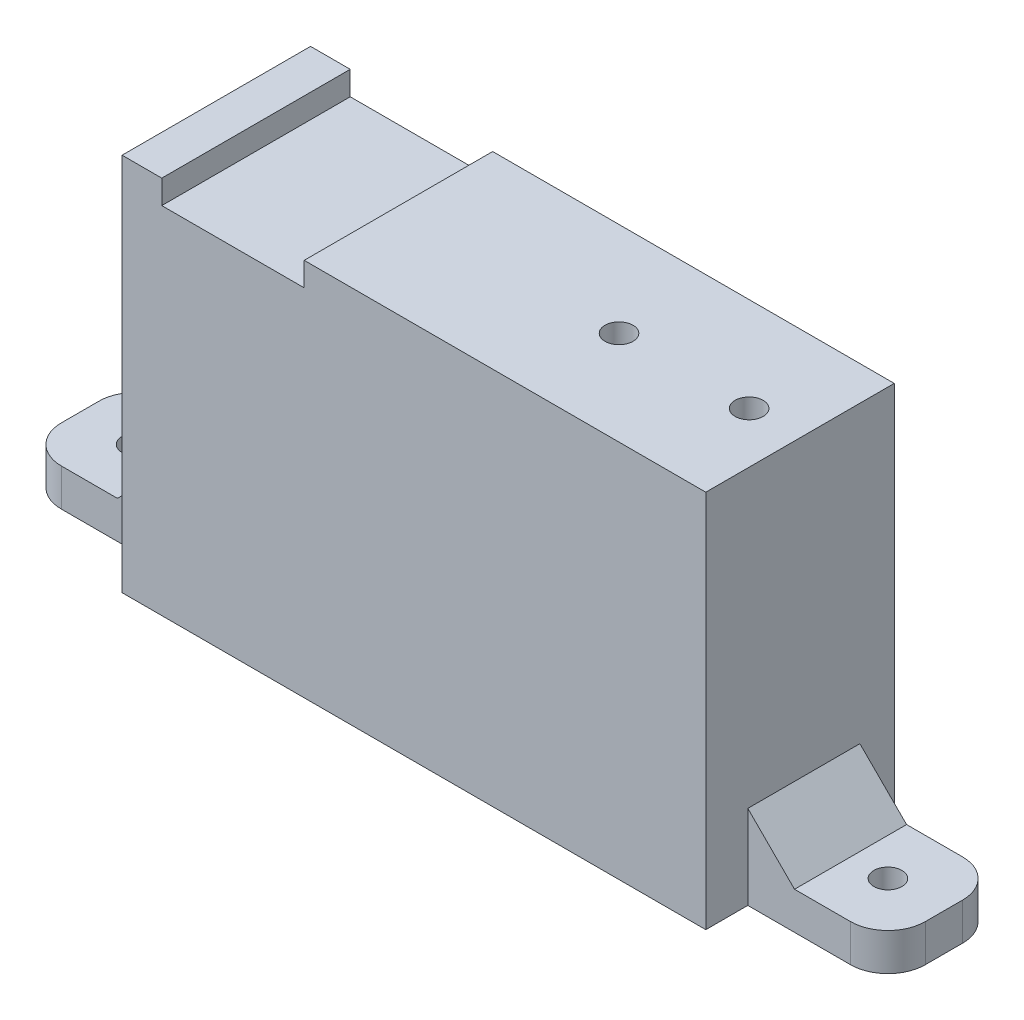
SolidWorks part; units mm, degrees
ref_plane "Спереди" through (0, 0, 0) normal (0, 0, 1) x (1, 0, 0)
ref_plane "Сверху" through (0, 0, 0) normal (0, 1, 0) x (1, 0, 0)
ref_plane "Справа" through (0, 0, 0) normal (1, 0, 0) x (0, 0, -1)
other "Configuration Table"
sketch "основание" plane through (0, 0, 0) normal (0, 1, 0) x (1, 0, 0)
  line L1 (-31.25, -10.09) -> (31.25, -10.09)
  line L2 (-31.25, -10.09) -> (-31.25, 10.09)
  line L3 (-31.25, 10.09) -> (31.25, 10.09)
  line L4 (31.25, -10.09) -> (31.25, 10.09)
  line L5 (-31.25, -10.09) -> (31.25, 10.09) construction
  line L6 (-31.25, 10.09) -> (31.25, -10.09) construction
  point P0 (0, 0)
  dimension "D1" = 20.18
  dimension "D2" = 62.5
extrude "Бобышка-Вытянуть1" add sketch "основание" along normal blind 40.57
sketch "Эскиз6" plane through (0, 40.57, 0) normal (0, 1, 0) x (1, 0, 0)
  line L0 (31.25, 10.09) -> (-31.25, 10.09) construction
  line L1 (-27, 10.09) -> (-11.75, 10.09)
  line L2 (-27, 10.09) -> (-27, -10.09)
  line L3 (-27, -10.09) -> (-11.75, -10.09)
  line L4 (-11.75, 10.09) -> (-11.75, -10.09)
  line L5 (-31.25, -10.09) -> (31.25, -10.09) construction
  dimension "D1" = 15.25
  dimension "D2" = 4.25
extrude "Вырез-Вытянуть1" cut sketch "Эскиз6" against normal blind 2.55
sketch "Эскиз7" plane through (0, 40.57, 0) normal (0, 1, 0) x (1, 0, 0)
  line L0 (0, 0) -> (46.5539, 0) construction
  line L2 (31.25, -10.09) -> (31.25, 10.09) construction
  circle A0 centre (25.8, 0) radius 1.5
  circle A1 centre (11.87, 0) radius 1.5
  point P7 (27.3, 0)
  point P10 (13.37, 0)
  point P11 (24.3, 0)
  dimension "D1" = 3
  dimension "D2" = 3
  dimension "D3" = 3.95
  dimension "D4" = 10.93
extrude "Вырез-Вытянуть2" cut sketch "Эскиз7" against normal blind 15 contours L0 A0 | A0 L0 | A1
sketch "Эскиз8" plane through (0, 0, 0) normal (0, -1, 0) x (1, 0, 0)
  line L0 (-31.25, -10.09) -> (-31.25, 10.09) construction
  line L1 (-31.25, 5.59) -> (-42.25, 5.59)
  line L2 (-31.25, 5.59) -> (-31.25, -6.41)
  line L3 (-31.25, -6.41) -> (-42.25, -6.41)
  line L4 (-46.25, 1.59) -> (-46.25, -2.41)
  line L5 (-31.25, 10.09) -> (31.25, 10.09) construction
  line L6 (0, 0) -> (0, 20.7226) construction
  line L7 (31.25, -6.41) -> (42.25, -6.41)
  line L8 (46.25, 1.59) -> (46.25, -2.41)
  line L9 (31.25, 5.59) -> (42.25, 5.59)
  line L10 (31.25, 5.59) -> (31.25, -6.41)
  circle A0 centre (-40.25, -0.41) radius 1.5
  circle A1 centre (40.25, -0.41) radius 1.5
  arc A2 (46.25, 1.59) -> (42.25, 5.59) centre (42.25, 1.59) ccw
  arc A3 (42.25, -6.41) -> (46.25, -2.41) centre (42.25, -2.41) ccw
  arc A4 (-46.25, 1.59) -> (-42.25, 5.59) centre (-42.25, 1.59) cw
  arc A5 (-42.25, -6.41) -> (-46.25, -2.41) centre (-42.25, -2.41) cw
  point P21 (46.25, 5.59)
  point P24 (46.25, -6.41)
  point P27 (-46.25, 5.59)
  point P30 (-46.25, -6.41)
  dimension "D4" = 3
  dimension "D7" = 4
  dimension "D8" = 4
  dimension "D9" = 4
  dimension "D10" = 4
  dimension "D1" = 15
  dimension "D2" = 12
  dimension "D3" = 4.5
  dimension "D5" = 6
  dimension "D6" = 6
extrude "Бобышка-Вытянуть2" add sketch "Эскиз8" against normal blind 4
chamfer "Фаска1" distance 5 angle 45 1 edges at (-31.25, 4, -0.41)
chamfer "Фаска2" distance 5 angle 45 1 edges at (31.25, 4, -0.41)
